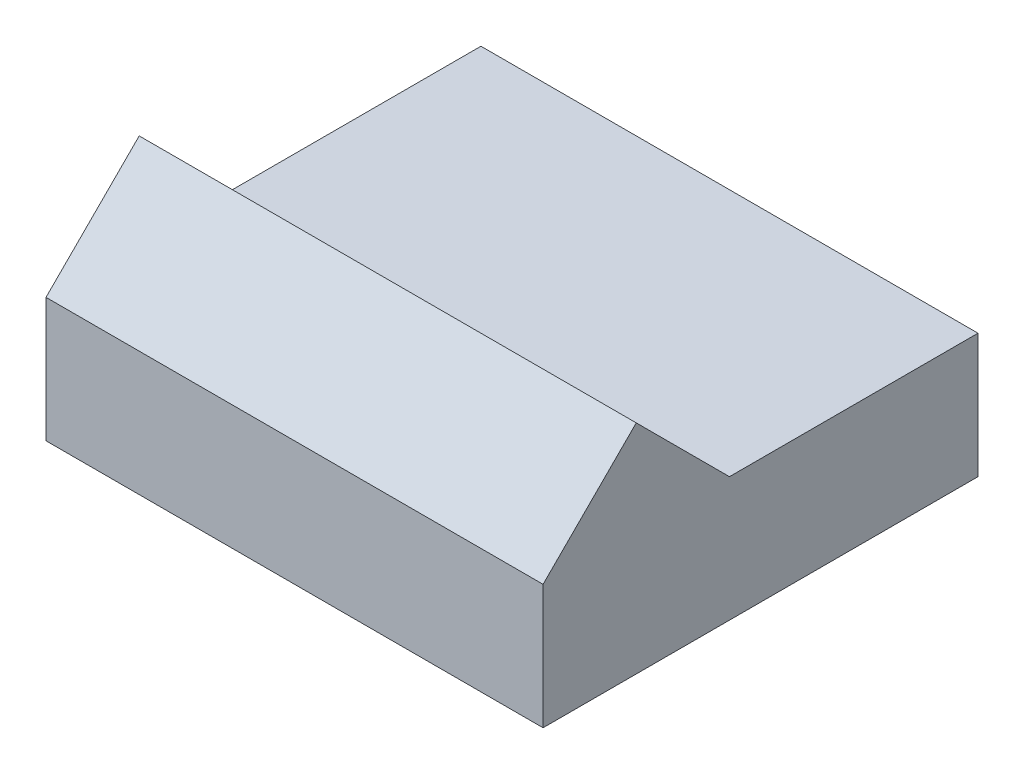
SolidWorks part; units mm, degrees
ref_plane "Front Plane" through (0, 0, 0) normal (0, 0, 1) x (1, 0, 0)
ref_plane "Top Plane" through (0, 0, 0) normal (0, 1, 0) x (1, 0, 0)
ref_plane "Right Plane" through (0, 0, 0) normal (1, 0, 0) x (0, 0, -1)
sketch "Sketch2" plane through (0, 0, 0) normal (1, 0, 0) x (0, 0, -1)
  line L1 (0.0003, 29.7963) -> (-6.9997, 29.7963)
  line L2 (0.0003, 29.7963) -> (0.0003, 27.7963)
  line L3 (0.0003, 27.7963) -> (-6.9997, 27.7963)
  line L4 (-6.9997, 29.7963) -> (-6.9997, 27.7963)
  line L5 (-3.9997, 29.7963) -> (-5.4997, 31.2963)
  line L6 (-5.4997, 31.2963) -> (-6.9997, 29.7963)
  dimension "D2" = 1.5
  dimension "D1" = 2
  dimension "D3" = 4
extrude "Boss-Extrude1" add sketch "Sketch2" along normal blind 8
